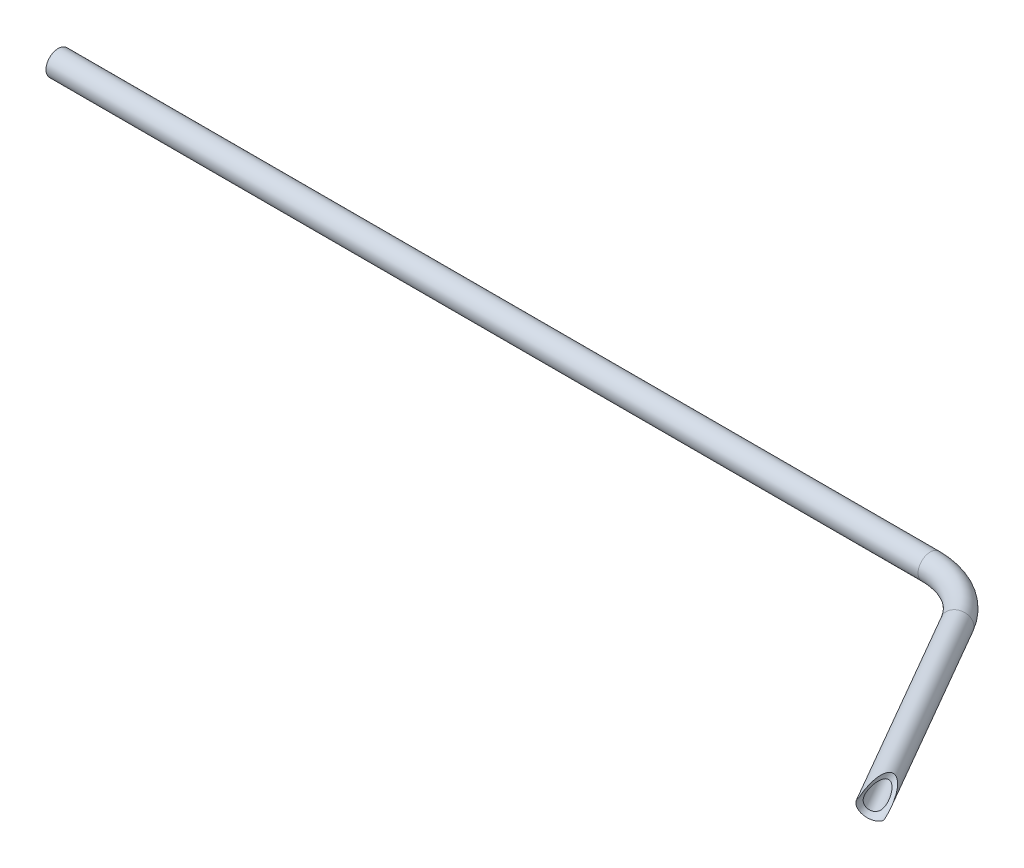
SolidWorks part; units mm, degrees
material "Stainless Steel 2205"
ref_plane "Front Plane" through (0, 0, 0) normal (0, 0, 1) x (1, 0, 0)
ref_plane "Top Plane" through (0, 0, 0) normal (0, 1, 0) x (1, 0, 0)
ref_plane "Right Plane" through (0, 0, 0) normal (1, 0, 0) x (0, 0, -1)
sketch "Sketch1" plane through (0, 0, 0) normal (0, 1, 0) x (1, 0, 0)
  line L0 (0, 0) -> (4300, 0) construction
  line L1 (4300, 0) -> (4300, -978.63) construction
  line L2 (0, 0) -> (3561.7826, 0)
  line L3 (3821.5902, -150) -> (4300, -978.63)
  arc A0 (3821.5902, -150) -> (3561.7826, 0) centre (3561.7826, -300) ccw
  point P7 (3734.9877, 0)
  dimension "D2" = 300
  dimension "D1" = 4300
  dimension "D3" = 120
  dimension "D4" = 978.63
sketch "Sketch2" plane through (0, 0, 0) normal (1, 0, 0) x (0, 0, -1)
  circle A0 centre (0, 0) radius 50
  circle A1 centre (0, 0) radius 35
  dimension "D1" = 100
  dimension "D2" = 15
sweep "Sweep1" add profiles "Sketch2" path "Sketch1"
sketch "Sketch3" plane through (0, 0, 0) normal (0, 1, 0) x (1, 0, 0)
  line L0 (4300, 0) -> (4300, -978.63)
  line L1 (4256.6987, -1003.63) -> (4343.3013, -953.63) construction
  line L2 (4300, 0) -> (0, 0)
ref_plane "Plane1" through (4300, 0, 0) normal (1, 0, 0) x (0, 0, -1)
sketch "Sketch4" plane through (4300, 0, 0) normal (1, 0, 0) x (0, 0, -1)
  line L0 (0, 0) -> (-978.63, 0)
  line L1 (0, 0) -> (-978.63, 0) construction
  line L2 (-978.63, 0) -> (-240.3615, 421.2497)
  line L3 (-240.3615, 421.2497) -> (0, 0)
  dimension "D1" = 485
ref_plane "Plane2" through (4300, 0, 978.63) normal (0, 0.4956, -0.8686) x (1, 0, 0)
sketch "Sketch5" plane through (4300, 0, 978.63) normal (0, 0.4956, -0.8686) x (1, 0, 0)
  circle A0 centre (0, 0) radius 50
  dimension "D1" = 100
extrude "Cut-Extrude1" cut sketch "Sketch5" against normal through all both and the other way through all
equation "\"hatchHoleDiameter\"= 600mm"
equation "\"hullThickness\"= 120mm"
equation "\"gasketHullInterconnectWidth\"= 100mm"
equation "\"collarThickness\"= 15"
equation "\"hatchTunnelLength\"=200"
equation "\"oRingDiameter\"=2"
equation "\"boltPatternRadiusInterconnect\"=500"
equation "\"interconnectBoltDiameter\"=30"
equation "\"hatchShaftDiameter\"=20"
equation "\"hatchMinima\"=50"
equation "\"hullDiameter\"=2000"
equation "\"hatchMaxima\"=180"
equation "\"bushingFlatHatch\"=15"
equation "\"hingePivotDiameter\"=20"
equation "\"handleWidth\"=250"
equation "\"handleHeight\"=160"
equation "\"handleThickness\"=25"
equation "\"FrameLength\"= 4300"
equation "\"FrameMidLength\"= 3000"
equation "\"TubeOD\"= 100"
equation "\"FrameBackFlat\"= 800"
equation "\"TubeWall\"=15"
equation "\"D1@Sketch1\"=\"FrameLength\""
equation "\"TopMemberAngle\"=120"
equation "\"D3@Sketch1\"=\"TopMemberAngle\""
equation "\"D1@Sketch2\"=\"TubeOD\""
equation "\"D2@Sketch2\"=\"TubeWall\""
equation "\"D1@Sketch4\"=\"hullThickness\"+\"hatchHoleDiameter\"/2 + \"collarThickness\"+\"TubeOD\"/2"
equation "\"D1@Sketch5\"=\"TubeOD\""
equation "\"FrameHight\"= 2500"
